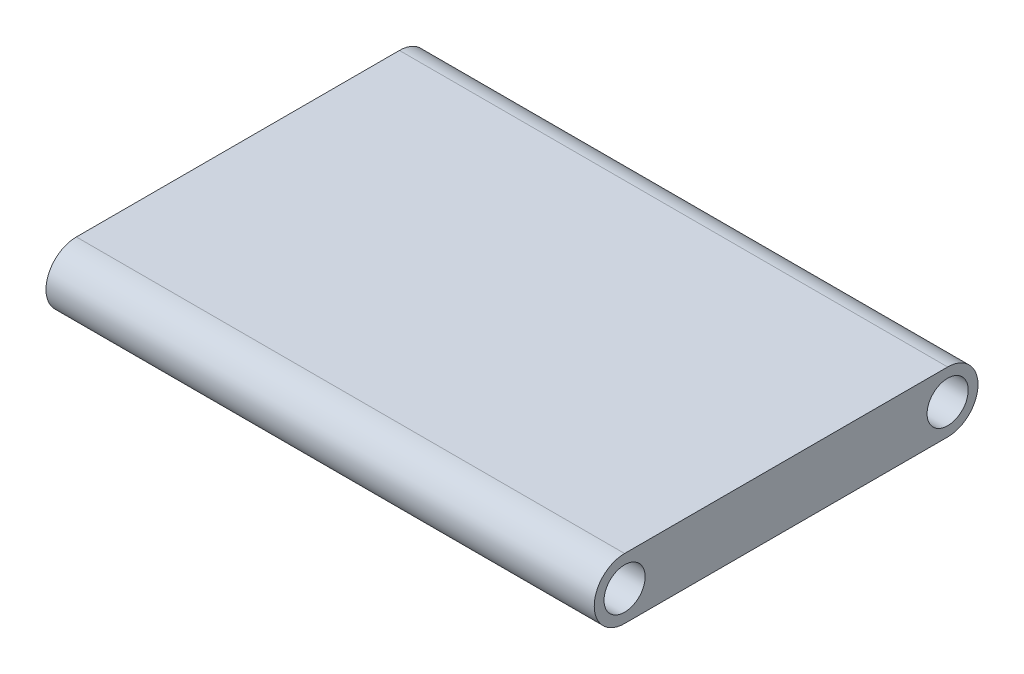
SolidWorks part; units mm, degrees
ref_plane "Front Plane" through (0, 0, 0) normal (0, 0, 1) x (1, 0, 0)
ref_plane "Top Plane" through (0, 0, 0) normal (0, 1, 0) x (1, 0, 0)
ref_plane "Right Plane" through (0, 0, 0) normal (1, 0, 0) x (0, 0, -1)
sketch "Sketch1" plane through (0, 0, 0) normal (0, 0, 1) x (1, 0, 0)
  line L0 (0, 225.6243) -> (0, -228.0744) construction
  line L1 (-321.0116, 119.163) -> (-306.0116, 119.163) construction
  line L2 (-572.0116, 119.163) -> (-332.0116, 119.163) construction
  line L3 (-586.0116, 119.163) -> (-586.0116, 157.7336) construction
  line L4 (-306.0116, 119.163) -> (-306.0116, 157.7336) construction
  circle A0 centre (-572.0116, 119.163) radius 4
  circle A1 centre (-332.0116, 119.163) radius 3
  circle A2 centre (-572.0116, 119.163) radius 14
  circle A3 centre (-332.0116, 119.163) radius 11
  point P16 (0, 0)
  dimension "D3" = 8
  dimension "D4" = 6
  dimension "D5" = 10
  dimension "D1" = 240
  dimension "D2" = 8
  dimension "D6" = 15
sketch "Sketch3" plane through (0, 0, 0) normal (0, 0, 1) x (1, 0, 0)
  line L0 (0, 36.8334) -> (-280, 36.8334)
  line L1 (-280, 36.8334) -> (-280, 67.8334)
  line L2 (-280, 67.8334) -> (0, 67.8334)
  line L3 (0, 225.6243) -> (0, -228.0744) construction
  line L4 (0, 67.8334) -> (0, 36.8334)
  point P7 (-280, 0)
  point P8 (0, 0)
  point P9 (0, 0)
  dimension "D1" = 280
  dimension "D2" = 31
extrude "Boss-Extrude1" add sketch "Sketch3" along normal blind 196
sketch "Sketch4" plane through (0, 0, 0) normal (1, 0, 0) x (0, 0, -1)
  line L0 (-196, 36.8334) -> (-196, 67.8334) construction
  line L1 (-98, 15.5) -> (-98, 75.5369) construction
  line L2 (-196, 67.8334) -> (0, 67.8334) construction
  line L3 (-180.5, 67.8334) -> (-180.5, 68.8334)
  line L4 (-180.5, 68.8334) -> (-197, 68.8334)
  line L5 (-197, 68.8334) -> (-197, 35.8334)
  line L6 (-197, 35.8334) -> (-180.5, 35.8334)
  line L7 (-180.5, 35.8334) -> (-180.5, 36.8334)
  line L8 (-196, 36.8334) -> (0, 36.8334) construction
  line L9 (-15.5, 67.8334) -> (-15.5, 68.8334)
  line L10 (-15.5, 68.8334) -> (1, 68.8334)
  line L11 (1, 68.8334) -> (1, 35.8334)
  line L12 (1, 35.8334) -> (-15.5, 35.8334)
  line L13 (-15.5, 35.8334) -> (-15.5, 36.8334)
  arc A0 (-180.5, 67.8334) -> (-180.5, 36.8334) centre (-180.5, 52.3334) ccw
  arc A2 (-15.5, 67.8334) -> (-15.5, 36.8334) centre (-15.5, 52.3334) cw
  point P4 (-196, 52.3334)
  point P5 (-196, 52.3334)
  point P10 (-98, 67.8334)
  dimension "D1" = 31
  dimension "D2" = 1
  dimension "D3" = 1
  dimension "D4" = 1
extrude "Cut-Extrude1" cut sketch "Sketch4" against normal through all both and the other way through all
sketch "Sketch6" plane through (0, 0, 0) normal (1, 0, 0) x (0, 0, -1)
  circle A0 centre (-180.5, 52.3334) radius 10.5
  arc A1 (-180.5, 67.8334) -> (-180.5, 36.8334) centre (-180.5, 52.3334) ccw construction
  circle A2 centre (-15.5, 52.3334) radius 10.5
  arc A3 (-15.5, 36.8334) -> (-15.5, 67.8334) centre (-15.5, 52.3334) ccw construction
  point P5 (-196, 52.3334)
  point P9 (0, 0)
  point P14 (0, 52.3334)
  dimension "D1" = 21
  dimension "D2" = 21
extrude "Cut-Extrude2" cut sketch "Sketch6" against normal blind 37
sketch "Sketch5" plane through (0, 67.8334, 0) normal (0, 1, 0) x (1, 0, 0)
  line L0 (-40, -98) -> (-280, -98) construction
  line L1 (0, -180.5) -> (0, -15.5) construction
  line L2 (-280, -180.5) -> (-280, -15.5) construction
  line L3 (-280, -108) -> (-223, -165)
  line L4 (-87, -165) -> (-87, -196)
  line L6 (-87, -196) -> (-280, -196)
  line L7 (0, -170) -> (18.3344, -170) construction
  line L8 (0, -165) -> (-223, -165) construction
  line L14 (0, -108) -> (-40.9855, -108) construction
  line L15 (-280, -108) -> (-280, -196)
  line L17 (-265.8579, -108) -> (-218.8579, -155)
  line L18 (-265.8579, -108) -> (-218.8579, -108)
  line L19 (-218.8579, -108) -> (-218.8579, -155)
  line L21 (-280, -196) -> (0, -196) construction
  line L22 (0, -170) -> (5.9136, -170) construction
  line L24 (-87, -196) -> (-280, -196)
  line L25 (-223, -165) -> (-87, -165)
  line L36 (-213.8579, -108) -> (-213.8579, -155)
  line L37 (-213.8579, -155) -> (-173.1547, -131.5)
  line L38 (-173.1547, -131.5) -> (-213.8579, -108)
  line L39 (-203.8579, -155) -> (-170.6547, -135.8301) construction
  line L46 (-203.8579, -108) -> (-170.6547, -127.1699) construction
  line L47 (-203.8579, -108) -> (-170.6547, -127.1699)
  line L48 (-203.8579, -155) -> (-170.6547, -135.8301)
  line L49 (-165.6547, -135.8301) -> (-132.4515, -155)
  line L50 (-203.8579, -155) -> (-170.6547, -155)
  line L51 (-203.8579, -108) -> (-170.6547, -108)
  line L52 (-165.6547, -127.1699) -> (-132.4515, -108)
  line L53 (-163.1547, -131.5) -> (-122.4515, -108)
  line L54 (-163.1547, -131.5) -> (-122.4515, -155)
  line L55 (-122.4515, -155) -> (-122.4515, -108)
  line L56 (-119.9515, -108) -> (-119.9515, -137.0752) construction
  line L57 (-76.7483, -131.5) -> (-117.4515, -155)
  line L58 (-76.7483, -131.5) -> (-117.4515, -108)
  line L59 (-117.4515, -155) -> (-117.4515, -108)
  line L60 (-107.4515, -155) -> (-10.1002, -98.7942)
  line L66 (-107.4515, -108) -> (-10.1002, -164.2058)
  line L69 (-170.6547, -108) -> (-170.6547, -127.1699)
  line L70 (-165.6547, -108) -> (-165.6547, -127.1699)
  line L71 (-170.6547, -143.9982) -> (-165.6547, -143.9982) construction
  line L72 (-166.325, -129.6696) -> (-108.9335, -162.8046) construction
  line L73 (-170.6547, -108) -> (-280, -108) construction
  line L74 (-165.6547, -108) -> (-132.4515, -108)
  line L75 (-168.1547, -134.3868) -> (-122.4515, -108) construction
  line L76 (-165.6547, -155) -> (-132.4515, -155)
  line L77 (-170.6547, -135.8301) -> (-170.6547, -155)
  line L78 (-10.1002, -108) -> (-10.1002, -164.2058)
  line L79 (-165.6547, -135.8301) -> (-165.6547, -155)
  line L82 (-10.1002, -108) -> (-107.4515, -108)
  line L83 (-10.1002, -108) -> (-165.6547, -108) construction
  line L84 (-10.1002, -155) -> (-107.4515, -155)
  line L85 (-10.1002, -98.7942) -> (-10.1002, -155)
  line L133 (-40, -223.0751) -> (-87, -223.0751) construction
  point P5 (-85.5433, -196)
  point P14 (-40, -165)
  point P58 (-168.1547, -143.9982)
  dimension "D1" = 10
  dimension "D3" = 47
  dimension "D4" = 5
  dimension "D5" = 45
  dimension "D6" = 10
  dimension "D8" = 10
  dimension "D9" = 5
  dimension "D10" = 60
  dimension "D11" = 60
  dimension "D12" = 5
  dimension "D13" = 5
  dimension "D14" = 2.5
  dimension "D15" = 5
  dimension "D16" = 5
  dimension "D17" = 5
  dimension "D21" = 5
  dimension "D23" = 240
  dimension "D24" = 47
sketch "Sketch7" plane through (0, 0, 0) normal (1, 0, 0) x (0, 0, -1)
  line L0 (-165, 36.8334) -> (-165, 62.8334)
  line L1 (-180.5, 36.8334) -> (-15.5, 36.8334) construction
  line L2 (-165, 62.8334) -> (-31, 62.8334)
  line L3 (-31, 62.8334) -> (-31, 36.8334)
  line L4 (-31, 36.8334) -> (-165, 36.8334)
  line L5 (-180.5, 67.8334) -> (-15.5, 67.8334) construction
  point P4 (0, 0)
  point P7 (-98, 62.8334)
  point P8 (-98, 36.8334)
  dimension "D1" = 134
  dimension "D2" = 5
sketch "Sketch8" plane through (0, 67.8334, 0) normal (0, 1, 0) x (1, 0, 0)
  line L0 (-280, -98) -> (-40, -98) construction
  line L1 (-280, -180.5) -> (-280, -15.5) construction
  point P6 (0, 0)
  dimension "D1" = 240
